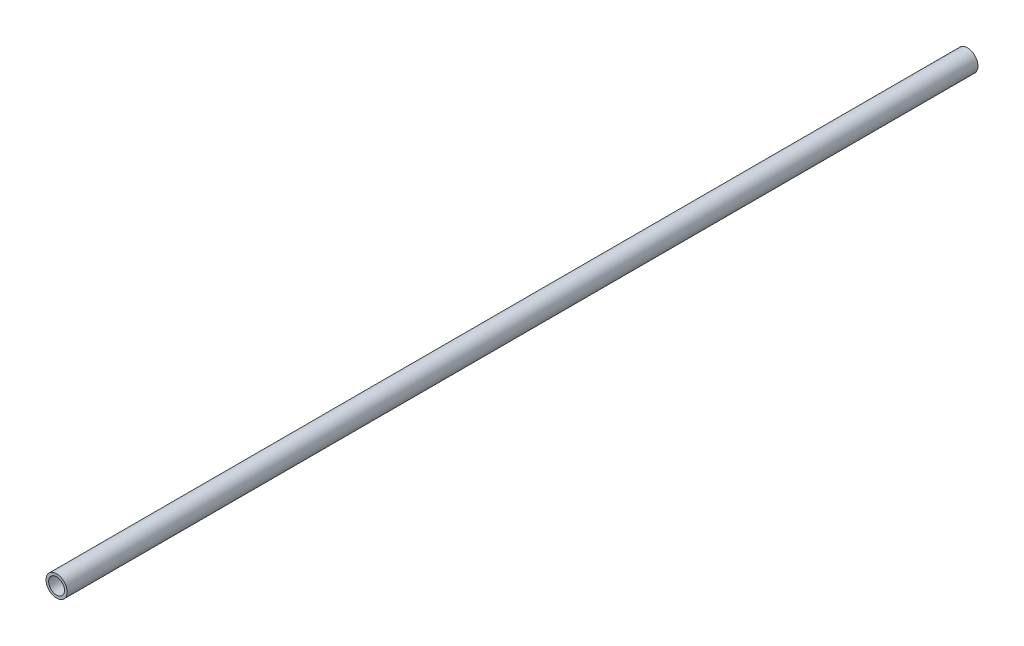
SolidWorks part; units mm, degrees
material "Thornel Mat VMA"
ref_plane "Front Plane" through (0, 0, 0) normal (0, 0, 1) x (1, 0, 0)
ref_plane "Top Plane" through (0, 0, 0) normal (0, 1, 0) x (1, 0, 0)
ref_plane "Right Plane" through (0, 0, 0) normal (1, 0, 0) x (0, 0, -1)
sketch "Sketch1" plane through (0, 0, 0) normal (0, 0, 1) x (1, 0, 0)
  circle A0 centre (0, 0) radius 2
  circle A1 centre (0, 0) radius 1.5
  dimension "D1" = 4
  dimension "D2" = 3
extrude "Boss-Extrude1" add sketch "Sketch1" along normal blind 172
